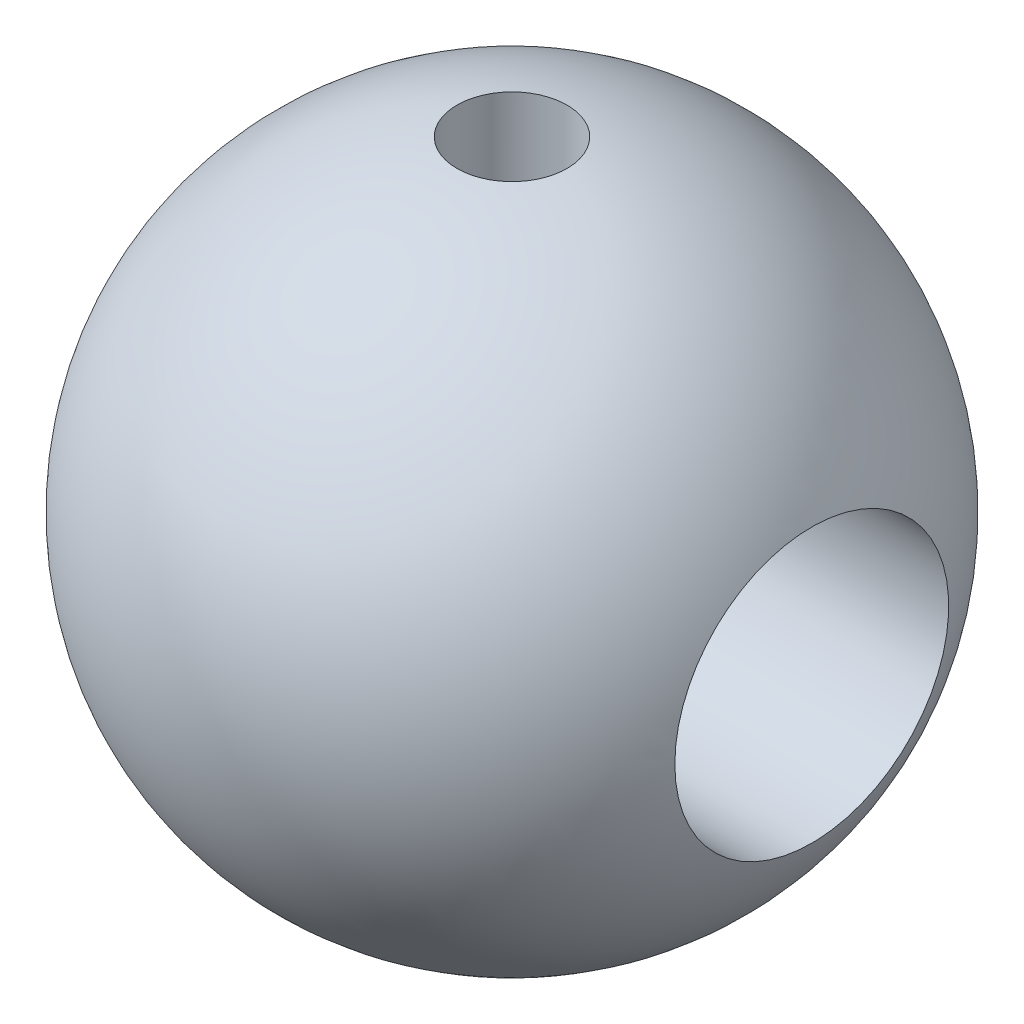
SolidWorks part; units mm, degrees
material "Alloy Steel"
ref_plane "Front Plane" through (0, 0, 0) normal (0, 0, 1) x (1, 0, 0)
ref_plane "Top Plane" through (0, 0, 0) normal (0, 1, 0) x (1, 0, 0)
ref_plane "Right Plane" through (0, 0, 0) normal (1, 0, 0) x (0, 0, -1)
sketch "Sketch1" plane through (0, 0, 0) normal (1, 0, 0) x (0, 0, -1)
  line L0 (1.59, 9.3964) -> (1.59, -9.3964)
  line L1 (0, 11.528) -> (0, -11.9866) construction
  arc A0 (1.59, -9.3964) -> (1.59, 9.3964) centre (0, 0) ccw
  dimension "D2" = 9.53
  dimension "D1" = 1.59
revolve "Revolve1" add sketch "Sketch1" angle 360 about L1
sketch "Sketch2" plane through (0, 0, 0) normal (0, 0, 1) x (1, 0, 0)
  line L1 (-12.7951, 0) -> (14.0578, 0)
  line L2 (-12.7951, 0) -> (-12.7951, 3.96)
  line L3 (-12.7951, 3.96) -> (14.0578, 3.96)
  line L4 (14.0578, 0) -> (14.0578, 3.96)
  dimension "D1" = 3.96
revolve "Cut-Revolve1" cut sketch "Sketch2" angle 360 about L1
